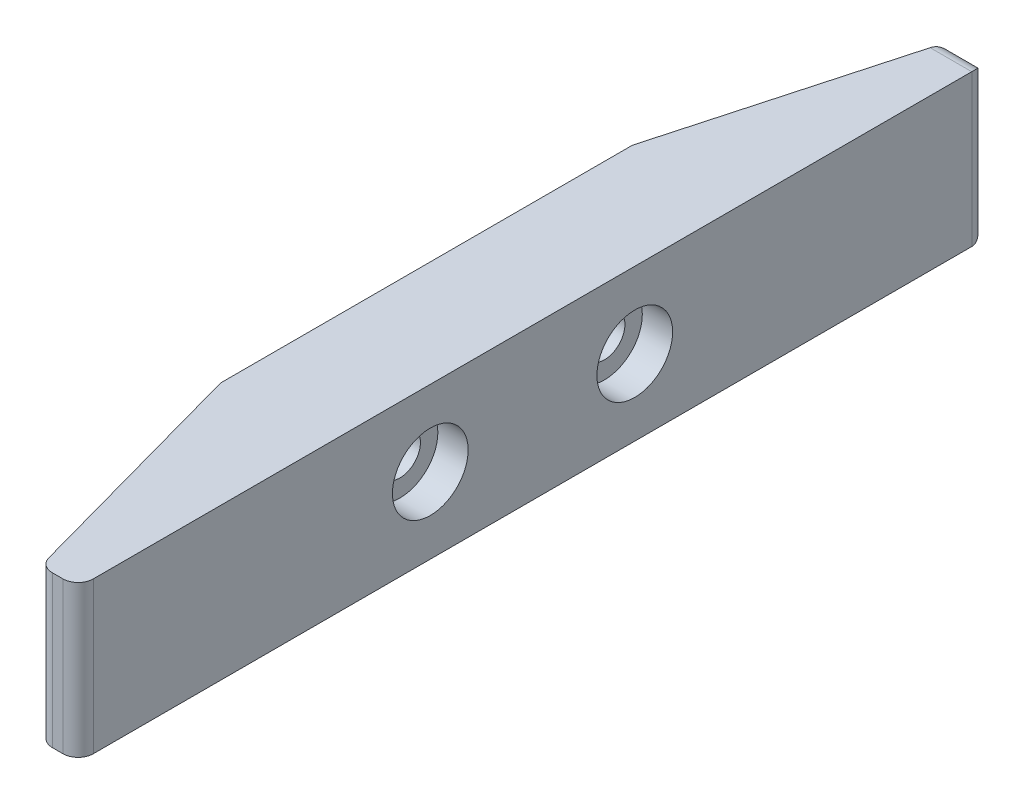
SolidWorks part; units mm, degrees
material "ABS"
ref_plane "Front Plane" through (0, 0, 0) normal (0, 0, 1) x (1, 0, 0)
ref_plane "Top Plane" through (0, 0, 0) normal (0, 1, 0) x (1, 0, 0)
ref_plane "Right Plane" through (0, 0, 0) normal (1, 0, 0) x (0, 0, -1)
other "Configuration Table"
sketch "Sketch1" plane through (0, 0, 0) normal (0, 1, 0) x (1, 0, 0)
  line L0 (0, 3.75) -> (0, -3.75) construction
  line L1 (0, 6.75) -> (4.3727, 6.75) construction
  line L2 (0, -6.75) -> (4.6131, -6.75) construction
  line L3 (0, 0) -> (33.5371, 0) construction
  line L4 (0, 8.25) -> (4, 8.25)
  line L5 (0, 8.25) -> (0, 5.25)
  line L6 (0, 5.25) -> (4, 5.25)
  line L7 (4, 8.25) -> (4, 5.25)
  line L8 (0, 8.25) -> (4, 5.25) construction
  line L9 (0, 5.25) -> (4, 8.25) construction
  line L10 (0, -5.25) -> (4, -5.25)
  line L11 (0, -5.25) -> (0, -8.25)
  line L12 (0, -8.25) -> (4, -8.25)
  line L13 (4, -5.25) -> (4, -8.25)
  line L14 (0, -5.25) -> (4, -8.25) construction
  line L15 (0, -8.25) -> (4, -5.25) construction
  line L16 (0, -30) -> (0, 30)
  line L17 (0, 30) -> (33.5371, 30)
  line L18 (0, -30) -> (33.5371, -30)
  line L19 (2, 6.75) -> (2, -6.75) construction
  line L20 (33.5371, 30) -> (33.5371, -30)
  point P2 (0, 0)
  point P8 (2, 6.75)
  point P13 (2, -6.75)
  line B0 (0, 3.75) -> (0, 9.75)
  line B1 (0, -9.75) -> (0, -3.75)
  dimension "D1" = 3
  dimension "D2" = 4
  dimension "D4" = 60
sketch_block_instance "Block2-1"
sketch_block "Block2"
extrude "Boss-Extrude1" add sketch "Sketch1" along normal blind 10
sketch "Sketch2" plane through (0, 0, 0) normal (-1, 0, 0) x (0, 0, 1)
  line L0 (0, 10) -> (0, 0) construction
  line L1 (30, 10) -> (-30, 10) construction
  line L2 (30, 0) -> (-30, 0) construction
  line L3 (0, 5) -> (-6.75, 5) construction
  circle A0 centre (-6.75, 5) radius 1.35
  circle A1 centre (6.75, 5) radius 1.35
  dimension "D2" = 2.7
  dimension "D1" = 6.75
extrude "Cut-Extrude1" cut sketch "Sketch2" against normal blind 10
ref_plane "Plane1" through (4, 0, 0) normal (-1, 0, 0) x (0, 0, 1)
sketch "Sketch5" plane through (0, 10, 0) normal (0, 1, 0) x (1, 0, 0)
  line L0 (0, 13.5911) -> (4.5305, 30)
  line L1 (0, -30) -> (0, 30) construction
  line L2 (0, 30) -> (33.5371, 30) construction
  line L3 (0, 13.5911) -> (0, 30)
  line L4 (0, 30) -> (4.5305, 30)
  line L5 (0, 0) -> (2.4293, 0) construction
  line L6 (0, -30) -> (4.5305, -30)
  line L7 (0, -13.5911) -> (0, -30)
  line L8 (0, -13.5911) -> (4.5305, -30)
  line L9 (0, -30) -> (33.5371, -30) construction
  point P14 (4.5305, 30)
extrude "Cut-Extrude3" cut sketch "Sketch5" against normal blind 18
sketch "Sketch7" plane through (0, 10, 0) normal (0, 1, 0) x (1, 0, 0)
  line L5 (13.5642, 28.5) -> (15.0639, 25.5146)
  line L6 (0, 0) -> (-5.2259, 0) construction
  line L7 (13.5642, -28.5) -> (15.0639, -25.5146)
  line L8 (4.9112, 29.5) -> (0.5, 13.5233)
  line L12 (4.9112, 29.5) -> (0.5, 13.5233)
  line L21 (0.5, 13.5233) -> (0.5, -13.5233)
  line L24 (0.5, 13.5233) -> (0.5, -13.5233)
  line L26 (0.5, -13.5233) -> (4.9112, -29.5)
  line L28 (0.5, -13.5233) -> (4.9112, -29.5)
  line L29 (4.9112, -29.5) -> (33.0371, -29.5)
  line L30 (4.9112, -29.5) -> (33.0371, -29.5)
  line L31 (33.0371, 29.5) -> (4.9112, 29.5)
  line L32 (33.0371, 29.5) -> (4.9112, 29.5)
  line L34 (33.0371, -29.5) -> (33.0371, 29.5)
  line L35 (33.0371, -29.5) -> (33.0371, 29.5)
  dimension "D1" = 0.5
sketch "Sketch10" plane through (0, 10, 0) normal (0, 1, 0) x (1, 0, 0)
  line L1 (13.2008, 31.1696) -> (34.0929, 31.1696)
  line L2 (13.2008, 31.1696) -> (13.2008, -33.023)
  line L3 (13.2008, -33.023) -> (34.0929, -33.023)
  line L4 (34.0929, 31.1696) -> (34.0929, -33.023)
extrude "Cut-Extrude4" cut sketch "Sketch10" against normal blind 26
sketch "Sketch15" plane through (0, 10, 0) normal (0, 1, 0) x (1, 0, 0)
  line L0 (4.5305, 30) -> (13.2008, 30) construction
  line L1 (7, 30) -> (13.2008, 30)
  line L2 (7, 30) -> (7, -30)
  line L3 (7, -30) -> (13.2008, -30)
  line L4 (13.2008, 30) -> (13.2008, -30)
  line L5 (0, -13.5911) -> (0, 13.5911) construction
  dimension "D1" = 7
extrude "Cut-Extrude5" cut sketch "Sketch15" against normal blind 26
fillet "Fillet1" radius 1 6 edges at (5.7653, 0, -30) (5.7653, 10, -30) (4.5305, 5, -30) (7, 5, -30) (7, 5, 30) (4.5305, 5, 30)
sketch "Sketch16" plane through (7, 0, 0) normal (1, 0, 0) x (0, 0, -1)
  circle A0 centre (-6.75, 5) radius 2.5
  circle A1 centre (6.75, 5) radius 2.5
  dimension "D1" = 5
extrude "Cut-Extrude6" cut sketch "Sketch16" against normal blind 2
